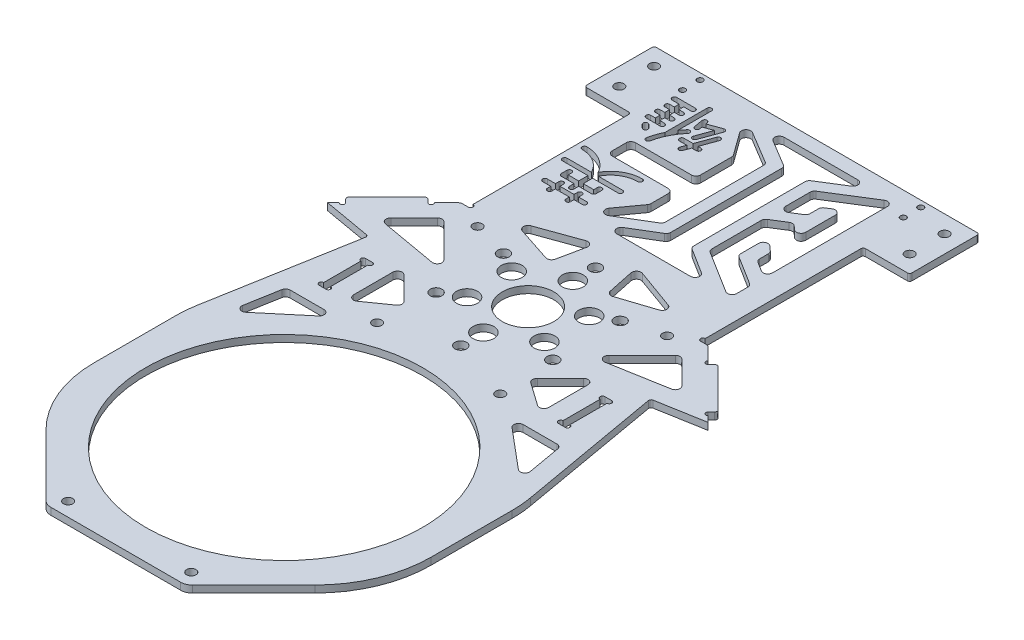
SolidWorks part; units mm, degrees
material "Thornel Mat VMA"
ref_plane "前视基准面" through (0, 0, 0) normal (0, 0, 1) x (1, 0, 0)
ref_plane "上视基准面" through (0, 0, 0) normal (0, 1, 0) x (1, 0, 0)
ref_plane "右视基准面" through (0, 0, 0) normal (1, 0, 0) x (0, 0, -1)
sketch "草图1" plane through (0, 0, 0) normal (0, 1, 0) x (1, 0, 0)
  line L0 (-72.5, 30.0305) -> (-60.7129, 96.8783)
  line L2 (0, 105) -> (0, 0) construction
  line L3 (-29.8887, -60) -> (20.992, -60) construction
  line L4 (30.0305, 72.5) -> (-30.0305, 72.5) construction
  line L5 (-30.0305, 72.5) -> (-72.5, 30.0305) construction
  line L6 (-72.5, 30.0305) -> (-72.5, -30.0305)
  line L7 (-72.5, -30.0305) -> (-30.0305, -72.5)
  line L8 (-30.0305, -72.5) -> (30.0305, -72.5)
  line L9 (30.0305, -72.5) -> (72.5, -30.0305)
  line L10 (72.5, -30.0305) -> (72.5, 30.0305)
  line L11 (72.5, 30.0305) -> (30.0305, 72.5) construction
  line L12 (0, 0) -> (-36.7354, 0) construction
  line L13 (-40.7839, 124.0178) -> (0, 105) construction
  line L14 (-89.43, 93.0743) -> (-127.5, 55.0043) construction
  line L15 (-127.5, 55.0043) -> (-127.5, 46.0679) construction
  line L16 (-78.0025, 104.5017) -> (-81.8916, 100.6126)
  line L17 (-60.3249, 122.1794) -> (-62.4462, 124.3007)
  line L18 (-53.2538, 129.2505) -> (-60.3249, 122.1794)
  line L19 (-81.8916, 100.6126) -> (-60.7129, 96.8783)
  line L20 (-53.2538, 129.2505) -> (-50, 129.2505)
  line L21 (0, -55) -> (0, 55) construction
  line L22 (72.5, 30.0305) -> (60.7129, 96.8783)
  line L23 (62.4462, 124.3007) -> (80.1238, 106.6231)
  line L24 (80.1238, 106.6231) -> (78.0025, 104.5017)
  line L26 (81.8916, 100.6126) -> (60.7129, 96.8783)
  line L27 (53.2538, 129.2505) -> (60.3249, 122.1794)
  line L28 (-80.1238, 106.6231) -> (-78.0025, 104.5017)
  line L29 (-62.4462, 124.3007) -> (-80.1238, 106.6231)
  line L30 (60.3249, 122.1794) -> (62.4462, 124.3007)
  line L31 (78.0025, 104.5017) -> (81.8916, 100.6126)
  line L33 (-50, 129.2505) -> (-50, 199.25)
  line L34 (-50, 199.25) -> (-70, 199.25)
  line L35 (-70, 199.25) -> (-70, 229.25)
  line L36 (-70, 229.25) -> (70, 229.25)
  line L37 (53.2538, 129.2505) -> (50, 129.2505)
  line L38 (50, 129.2505) -> (50, 199.25)
  line L39 (50, 199.25) -> (70, 199.25)
  line L40 (70, 199.25) -> (70, 229.25)
  line L41 (-62.5, 221.75) -> (-62.5, 206.75) construction
  line L42 (-47.5, 226.5) -> (-47.5, 219) construction
  circle A1 centre (0, 0) radius 59.6
  circle A3 centre (0, 105) radius 11.1
  circle A6 centre (-26.5, -66.5) radius 2
  circle A9 centre (26.5, -66.5) radius 2
  circle A11 centre (0, 0) radius 72.5 construction
  circle A12 centre (26.5, 66.5) radius 2
  circle A13 centre (-26.5, 66.5) radius 2
  circle A15 centre (-40.7839, 124.0178) radius 2
  circle A16 centre (40.7839, 124.0178) radius 2
  circle A19 centre (-62.5, 221.75) radius 2
  circle A20 centre (-62.5, 206.75) radius 2
  circle A21 centre (62.5, 206.75) radius 2
  circle A22 centre (62.5, 221.75) radius 2
  circle A24 centre (-47.5, 226.5) radius 1.25
  circle A26 centre (-47.5, 219) radius 1.25
  circle A27 centre (47.5, 219) radius 1.25
  circle A28 centre (47.5, 226.5) radius 1.25
  dimension "D2" = 119.2
  dimension "D3" = 53
  dimension "D4" = 22.2
  dimension "D6" = 60
  dimension "D7" = 4
  dimension "D10" = 145
  dimension "D8" = 6.5
  dimension "D9" = 4
  dimension "D22" = 50
  dimension "D26" = 4
  dimension "D27" = 15
  dimension "D30" = 2.75
  dimension "D32" = 2.5
  dimension "D23" = 229.25
  dimension "D5" = 105
  dimension "D11" = 45
  dimension "D12" = 115
  dimension "D13" = 129.05
  dimension "D14" = 5.5
  dimension "D15" = 127.5
  dimension "D16" = 70
  dimension "D17" = 135
  dimension "D18" = 3
  dimension "D19" = 25
  dimension "D20" = 10
  dimension "D21" = 35
  dimension "D24" = 30
  dimension "D25" = 20
  dimension "D28" = 7.5
  dimension "D29" = 7.5
  dimension "D31" = 15
  dimension "D33" = 7.5
extrude "凸台-拉伸1" add sketch "草图1" along normal blind 3
sketch "草图2" plane through (0, 3, 0) normal (0, 1, 0) x (1, 0, 0)
  line L0 (0, 155) -> (0, 85.2716) construction
  line L3 (0, 0) -> (0, -72.5) construction
  line L15 (-30.0305, -72.5) -> (30.0305, -72.5) construction
  line L17 (0, -55) -> (0, 55) construction
  line L18 (-53, 88) -> (-50, 88)
  line L19 (-53, 88) -> (-53, 68)
  line L20 (-53, 68) -> (-50, 68)
  line L21 (-50, 88) -> (-50, 68)
  line L22 (50, 88) -> (50, 68)
  line L23 (53, 68) -> (50, 68)
  line L24 (53, 88) -> (53, 68)
  line L36 (53, 88) -> (50, 88)
  circle A9 centre (0, 134) radius 2.5
  circle A10 centre (0, 124.25) radius 4.5
  circle A11 centre (0, 105) radius 29 construction
  circle A12 centre (0, 105) radius 19.25 construction
  circle A14 centre (25.1147, 119.5) radius 2.5
  circle A15 centre (16.671, 114.625) radius 4.5
  circle A16 centre (25.1147, 90.5) radius 2.5
  circle A17 centre (16.671, 95.375) radius 4.5
  circle A18 centre (0, 76) radius 2.5
  circle A19 centre (0, 85.75) radius 4.5
  circle A20 centre (-25.1147, 90.5) radius 2.5
  circle A21 centre (-16.671, 95.375) radius 4.5
  circle A22 centre (-25.1147, 119.5) radius 2.5
  circle A23 centre (-16.671, 114.625) radius 4.5
  dimension "D1" = 9
  dimension "D2" = 5
  dimension "D4" = 38.5
  dimension "D5" = 58
  dimension "D6" = 100
  dimension "D10" = 3
  dimension "D3" = 6
  dimension "D11" = 68
  dimension "D16" = 20
extrude "切除-拉伸4" cut sketch "草图2" against normal through all
sketch "草图3" plane through (0, 3, 0) normal (0, 1, 0) x (1, 0, 0)
  line L0 (-53, 88) -> (-53, 68) construction
  line L1 (-50, 68) -> (-50, 88) construction
  line L2 (-78.0025, 104.5017) -> (-81.8916, 100.6126) construction
  line L3 (-53.2538, 129.2505) -> (-60.3249, 122.1794) construction
  line L4 (-50, 199.25) -> (-50, 129.2505) construction
  line L8 (0, -1.65) -> (0, 1.65) construction
  circle A0 centre (-53, 87) radius 1
  circle A1 centre (-50, 87) radius 1
  circle A2 centre (-53, 69) radius 1
  circle A3 centre (-50, 69) radius 1
  circle A20 centre (50, 69) radius 1
  circle A21 centre (53, 69) radius 1
  circle A22 centre (50, 87) radius 1
  circle A23 centre (53, 87) radius 1
  circle A24 centre (-78.7096, 103.7946) radius 1
  circle A25 centre (-59.6177, 122.8865) radius 1
  circle A26 centre (59.6177, 122.8865) radius 1
  circle A27 centre (78.7096, 103.7946) radius 1
  circle A28 centre (-50, 130.2505) radius 1
  circle A29 centre (50, 130.2505) radius 1
  dimension "D1" = 2
extrude "切除-拉伸5" cut sketch "草图3" against normal through all
sketch "草图4" plane through (0, 3, 0) normal (0, 1, 0) x (1, 0, 0)
  line L0 (-59.0922, 60) -> (-37.3955, 60)
  line L1 (-37.3955, 60) -> (-62.8597, 38.6329)
  line L2 (-62.8597, 38.6329) -> (-59.0922, 60)
  line L3 (-51.2259, 119.9646) -> (-31.0288, 99.7676)
  line L4 (-31.0288, 99.7676) -> (-65.368, 105.8225)
  line L5 (-65.368, 105.8225) -> (-51.2259, 119.9646)
  line L6 (-42, 93.5787) -> (-42, 68)
  line L7 (-42, 68) -> (-27, 78.5787)
  line L8 (-27, 78.5787) -> (-42, 93.5787)
  line L9 (-60.7129, 96.8783) -> (-72.5, 30.0305) construction
  line L10 (40, 151.25) -> (40, 160.6877)
  line L11 (-81.8916, 100.6126) -> (-60.7129, 96.8783) construction
  line L12 (-53.2538, 129.2505) -> (-58.9106, 123.5936) construction
  line L13 (-53, 68) -> (-50, 68) construction
  line L14 (-50, 70) -> (-50, 86) construction
  line L15 (40, 223.25) -> (18, 209.4808)
  line L16 (18, 209.4808) -> (18, 194.3138)
  line L17 (18, 194.3138) -> (26, 199.3208)
  line L18 (26, 199.3208) -> (26, 205.0501)
  line L19 (26, 205.0501) -> (32, 208.8053)
  line L20 (32, 208.8053) -> (32, 188.0557)
  line L21 (32, 188.0557) -> (26, 193.4222)
  line L22 (26, 193.4222) -> (18, 188.4152)
  line L23 (18, 188.4152) -> (18, 165.0192)
  line L24 (18, 165.0192) -> (40, 151.25)
  line L25 (32, 171.5932) -> (32, 177.3225)
  line L26 (32, 177.3225) -> (26, 182.6891)
  line L27 (26, 182.6891) -> (26, 169.4499)
  line L28 (26, 169.4499) -> (40, 160.6877)
  line L29 (30.5755, 151.25) -> (-15.2962, 151.25)
  line L30 (-15.2962, 151.25) -> (3, 162.25)
  line L31 (3, 162.25) -> (3, 212.25)
  line L32 (3, 212.25) -> (-15.2962, 223.25)
  line L33 (-15.2962, 223.25) -> (30.5755, 223.25)
  line L34 (30.5755, 223.25) -> (13, 212.25)
  line L35 (13, 212.25) -> (13, 162.25)
  line L36 (13, 162.25) -> (30.5755, 151.25)
  line L45 (-25, 151.25) -> (-2, 165.078)
  line L50 (-2, 165.078) -> (-2, 209.422)
  line L51 (-2, 209.422) -> (-25, 223.25)
  line L52 (-25, 223.25) -> (-12, 205.25)
  line L53 (-12, 205.25) -> (-12, 189.25)
  line L54 (-12, 189.25) -> (-40, 189.25)
  line L55 (-40, 189.25) -> (-40, 179.25)
  line L56 (-40, 179.25) -> (-12, 179.25)
  line L57 (-12, 179.25) -> (-12, 169.25)
  line L58 (-12, 169.25) -> (-25, 151.25)
  line L59 (32, 171.5932) -> (40, 166.5862)
  line L62 (40, 166.5862) -> (40, 223.25)
  line L63 (0, -1.65) -> (0, 1.65) construction
  line L64 (27, 78.5787) -> (42, 93.5787)
  line L65 (42, 68) -> (27, 78.5787)
  line L66 (42, 93.5787) -> (42, 68)
  line L67 (65.368, 105.8225) -> (51.2259, 119.9646)
  line L68 (31.0288, 99.7676) -> (65.368, 105.8225)
  line L69 (51.2259, 119.9646) -> (31.0288, 99.7676)
  line L70 (62.8597, 38.6329) -> (59.0922, 60)
  line L71 (37.3955, 60) -> (62.8597, 38.6329)
  line L72 (59.0922, 60) -> (37.3955, 60)
  line L73 (70, 229.25) -> (-70, 229.25) construction
  line L74 (13, 187.25) -> (3, 187.25) construction
  line L75 (8, 151.25) -> (8, 223.25) construction
  line L76 (32, 188.0557) -> (26, 182.6891) construction
  line L77 (-50, 199.25) -> (-50, 131.2505) construction
  line L78 (50, 131.2505) -> (50, 199.25) construction
  line L79 (-35, 133.7936) -> (-8.7895, 143.25)
  line L80 (-8.7895, 143.25) -> (-12.3301, 126.3564)
  line L81 (-12.3301, 126.3564) -> (-35, 133.7936)
  line L82 (-24.3354, 121.8754) -> (-15.2682, 118.9008) construction
  line L83 (-4.4043, 125.1731) -> (-2.4468, 134.5128) construction
  line L85 (12.3301, 126.3564) -> (35, 133.7936)
  line L86 (8.7895, 143.25) -> (12.3301, 126.3564)
  line L87 (35, 133.7936) -> (8.7895, 143.25)
  circle A0 centre (-25.1147, 119.5) radius 2.5 construction
  circle A1 centre (-16.671, 114.625) radius 4.5 construction
  circle A2 centre (0, 134) radius 2.5 construction
  circle A3 centre (0, 124.25) radius 4.5 construction
  point P18 (8, 187.25)
  point P92 (-3.4256, 129.8429)
  point P94 (0, 229.25)
  point P101 (8, 187.25)
  dimension "D1" = 8
  dimension "D2" = 8
  dimension "D3" = 8
  dimension "D4" = 8
  dimension "D5" = 70
  dimension "D6" = 8
  dimension "D7" = 15
  dimension "D8" = 15
  dimension "D9" = 20
  dimension "D10" = 78
  dimension "D11" = 6
  dimension "D12" = 10
  dimension "D13" = 5
  dimension "D14" = 5
  dimension "D15" = 5
  dimension "D16" = 10
  dimension "D17" = 10
  dimension "D18" = 10
  dimension "D19" = 5
  dimension "D20" = 5
  dimension "D21" = 5
  dimension "D22" = 10
  dimension "D23" = 5
  dimension "D24" = 5
  dimension "D25" = 50
  dimension "D26" = 10
  dimension "D27" = 8
  dimension "D28" = 8
  dimension "D29" = 8
  dimension "D30" = 8
  dimension "D31" = 8
  dimension "D32" = 8
  dimension "D33" = 15
  dimension "D34" = 8
  dimension "D35" = 8
  dimension "D36" = 8
  dimension "D37" = 15
  dimension "D38" = 8
extrude "切除-拉伸7" cut sketch "草图4" against normal through all
sketch "草图5" plane through (0, 3, 0) normal (0, 1, 0) x (1, 0, 0)
  line L1 (-26.5, 155.75) -> (-43.5, 155.75) construction
  line L2 (-26.5, 154.75) -> (-43.5, 154.75)
  line L3 (-26.5, 156.75) -> (-43.5, 156.75)
  line L4 (-31, 153.25) -> (-31, 158.25) construction
  line L5 (-32, 153.25) -> (-32, 158.25)
  line L6 (-30, 153.25) -> (-30, 158.25)
  line L7 (-35, 167.75) -> (-35, 158.75) construction
  line L10 (-28.5, 161.75) -> (-28.5, 164.25) construction
  line L11 (-29.5, 161.75) -> (-29.5, 164.25)
  line L12 (-27.5, 161.75) -> (-27.5, 164.25)
  line L13 (-28.5, 161.75) -> (-41.5, 161.75) construction
  line L14 (-28.5, 160.75) -> (-41.5, 160.75)
  line L15 (-28.5, 162.75) -> (-41.5, 162.75)
  line L16 (-23, 167.75) -> (-47, 167.75) construction
  line L19 (-23, 166.75) -> (-47, 166.75)
  line L20 (-23, 168.75) -> (-47, 168.75)
  line L21 (-50, 199.25) -> (-50, 131.2505) construction
  line L22 (-18.1026, 152.25) -> (-34, 152.25) construction
  line L23 (-34, 167.75) -> (-34, 158.75)
  line L24 (-36, 167.75) -> (-36, 158.75)
  line L25 (-23, 177.25) -> (-47, 177.25) construction
  line L26 (-35, 158.75) -> (-35, 155.75) construction
  line L27 (-41.5, 161.75) -> (-41.5, 164.25) construction
  line L28 (-40.5, 161.75) -> (-40.5, 164.25)
  line L29 (-42.5, 161.75) -> (-42.5, 164.25)
  line L30 (-39, 153.25) -> (-39, 158.25) construction
  line L31 (-38, 153.25) -> (-38, 158.25)
  line L32 (-40, 153.25) -> (-40, 158.25)
  line L33 (-40, 179.25) -> (-12, 179.25) construction
  line L34 (-21.9414, 200.3358) -> (-29.2258, 200.3358) construction
  line L35 (-21.9414, 199.3358) -> (-29.2258, 199.3358)
  line L36 (-21.9414, 201.3358) -> (-29.2258, 201.3358)
  line L37 (-27.0526, 203.8358) -> (-23.9039, 212.4867) construction
  line L38 (-27.9923, 204.1778) -> (-24.8436, 212.8288)
  line L39 (-26.1129, 203.4938) -> (-22.9642, 212.1447)
  line L40 (-23.9039, 212.4867) -> (-30.6527, 210.0304) construction
  line L41 (-23.5619, 211.547) -> (-30.3107, 209.0907)
  line L42 (-24.2459, 213.4264) -> (-30.9947, 210.9701)
  line L43 (-25.8758, 196.8358) -> (-21.6411, 208.4706) construction
  line L44 (-26.8155, 197.1778) -> (-22.5808, 208.8126)
  line L45 (-24.9361, 196.4938) -> (-20.7014, 208.1286)
  line L46 (-30.3054, 208.0608) -> (-31, 212) construction
  line L47 (-31.2902, 207.8871) -> (-31.9848, 211.8264)
  line L48 (-29.3206, 208.2344) -> (-30.0152, 212.1736)
  line L49 (-34.5, 199.2589) -> (-34.5, 217.5) construction
  line L50 (-35.5, 199.2589) -> (-35.5, 217.5)
  line L51 (-33.5, 199.2589) -> (-33.5, 217.5)
  line L52 (-41.2929, 196.8358) -> (-42.7071, 198.25) construction
  line L53 (-42, 196.1287) -> (-43.4142, 197.5429)
  line L54 (-40.5858, 197.5429) -> (-42, 198.9571)
  line L55 (-39, 201.75) -> (-45, 201.75) construction
  line L56 (-39, 200.75) -> (-45, 200.75)
  line L57 (-39, 202.75) -> (-45, 202.75)
  line L58 (-42, 201.75) -> (-42, 214) construction
  line L59 (-43, 201.75) -> (-43, 214)
  line L60 (-41, 201.75) -> (-41, 214)
  line L61 (-38, 214) -> (-46, 214) construction
  line L62 (-38, 213) -> (-46, 213)
  line L63 (-38, 215) -> (-46, 215)
  line L64 (-39, 205.8333) -> (-45, 205.8333) construction
  line L65 (-39, 204.8333) -> (-45, 204.8333)
  line L66 (-39, 206.8333) -> (-45, 206.8333)
  line L67 (-39, 209.9167) -> (-45, 209.9167) construction
  line L68 (-39, 208.9167) -> (-45, 208.9167)
  line L69 (-39, 210.9167) -> (-45, 210.9167)
  line L70 (-45, 205.8333) -> (-45, 209.9167) construction
  line L71 (-70, 199.25) -> (-50, 199.25) construction
  line L72 (-12.0596, 188.2395) -> (-30.8607, 201.4878) construction
  line L73 (-12, 189.25) -> (-40, 189.25) construction
  line L74 (-21.6411, 208.4706) -> (-24.93, 209.6677) construction
  arc A0 (-26.5, 154.75) -> (-26.5, 156.75) centre (-26.5, 155.75) ccw
  arc A1 (-43.5, 156.75) -> (-43.5, 154.75) centre (-43.5, 155.75) ccw
  arc A2 (-32, 153.25) -> (-30, 153.25) centre (-31, 153.25) ccw
  arc A3 (-30, 158.25) -> (-32, 158.25) centre (-31, 158.25) ccw
  arc A6 (-29.5, 161.75) -> (-27.5, 161.75) centre (-28.5, 161.75) ccw
  arc A7 (-27.5, 164.25) -> (-29.5, 164.25) centre (-28.5, 164.25) ccw
  arc A8 (-28.5, 160.75) -> (-28.5, 162.75) centre (-28.5, 161.75) ccw
  arc A9 (-41.5, 162.75) -> (-41.5, 160.75) centre (-41.5, 161.75) ccw
  arc A12 (-23, 166.75) -> (-23, 168.75) centre (-23, 167.75) ccw
  arc A13 (-47, 168.75) -> (-47, 166.75) centre (-47, 167.75) ccw
  arc A14 (-35, 167.75) -> (-23, 176.25) centre (-23, 163.5294) cw construction
  arc A19 (-34, 167.75) -> (-36, 167.75) centre (-35, 167.75) ccw
  arc A20 (-36, 158.75) -> (-34, 158.75) centre (-35, 158.75) ccw
  arc A21 (-23, 177.25) -> (-35.9434, 168.0818) centre (-23, 163.5294) ccw
  arc A26 (-40.5, 161.75) -> (-42.5, 161.75) centre (-41.5, 161.75) cw
  arc A27 (-42.5, 164.25) -> (-40.5, 164.25) centre (-41.5, 164.25) cw
  arc A28 (-38, 153.25) -> (-40, 153.25) centre (-39, 153.25) cw
  arc A29 (-40, 158.25) -> (-38, 158.25) centre (-39, 158.25) cw
  arc A30 (-23, 175.25) -> (-34.0566, 167.4182) centre (-23, 163.5294) ccw
  arc A31 (-23, 175.25) -> (-23, 177.25) centre (-23, 176.25) ccw
  arc A32 (-35.9434, 168.0818) -> (-34.0566, 167.4182) centre (-35, 167.75) ccw
  arc A33 (-35, 167.75) -> (-47, 176.25) centre (-47, 163.5294) ccw construction
  arc A34 (-47, 177.25) -> (-34.0566, 168.0818) centre (-47, 163.5294) cw
  arc A35 (-47, 175.25) -> (-35.9434, 167.4182) centre (-47, 163.5294) cw
  arc A36 (-47, 175.25) -> (-47, 177.25) centre (-47, 176.25) cw
  arc A37 (-34.0566, 168.0818) -> (-35.9434, 167.4182) centre (-35, 167.75) cw
  arc A38 (-21.9414, 199.3358) -> (-21.9414, 201.3358) centre (-21.9414, 200.3358) ccw
  arc A39 (-29.2258, 201.3358) -> (-29.2258, 199.3358) centre (-29.2258, 200.3358) ccw
  arc A40 (-27.9923, 204.1778) -> (-26.1129, 203.4938) centre (-27.0526, 203.8358) ccw
  arc A41 (-22.9642, 212.1447) -> (-24.8436, 212.8288) centre (-23.9039, 212.4867) ccw
  arc A42 (-23.5619, 211.547) -> (-24.2459, 213.4264) centre (-23.9039, 212.4867) ccw
  arc A43 (-30.9947, 210.9701) -> (-30.3107, 209.0907) centre (-30.6527, 210.0304) ccw
  arc A44 (-26.8155, 197.1778) -> (-24.9361, 196.4938) centre (-25.8758, 196.8358) ccw
  arc A45 (-20.7014, 208.1286) -> (-22.5808, 208.8126) centre (-21.6411, 208.4706) ccw
  arc A46 (-31.2902, 207.8871) -> (-29.3206, 208.2344) centre (-30.3054, 208.0608) ccw
  arc A47 (-30.0152, 212.1736) -> (-31.9848, 211.8264) centre (-31, 212) ccw
  arc A48 (-36.5523, 193.25) -> (-31, 204.557) centre (-12.0596, 188.2395) cw construction
  arc A49 (-31.7576, 205.2097) -> (-37.5321, 193.4504) centre (-12.0596, 188.2395) ccw
  arc A50 (-30.2424, 203.9043) -> (-35.5726, 193.0496) centre (-12.0596, 188.2395) ccw
  arc A51 (-30.2424, 203.9043) -> (-31.7576, 205.2097) centre (-31, 204.557) ccw
  arc A52 (-37.5321, 193.4504) -> (-35.5726, 193.0496) centre (-36.5523, 193.25) ccw
  arc A53 (-35.5, 199.2589) -> (-33.5, 199.2589) centre (-34.5, 199.2589) ccw
  arc A54 (-33.5, 217.5) -> (-35.5, 217.5) centre (-34.5, 217.5) ccw
  arc A55 (-42, 196.1287) -> (-40.5858, 197.5429) centre (-41.2929, 196.8358) ccw
  arc A56 (-42, 198.9571) -> (-43.4142, 197.5429) centre (-42.7071, 198.25) ccw
  arc A57 (-39, 200.75) -> (-39, 202.75) centre (-39, 201.75) ccw
  arc A58 (-45, 202.75) -> (-45, 200.75) centre (-45, 201.75) ccw
  arc A59 (-43, 201.75) -> (-41, 201.75) centre (-42, 201.75) ccw
  arc A60 (-41, 214) -> (-43, 214) centre (-42, 214) ccw
  arc A61 (-38, 213) -> (-38, 215) centre (-38, 214) ccw
  arc A62 (-46, 215) -> (-46, 213) centre (-46, 214) ccw
  arc A63 (-39, 204.8333) -> (-39, 206.8333) centre (-39, 205.8333) ccw
  arc A64 (-45, 206.8333) -> (-45, 204.8333) centre (-45, 205.8333) ccw
  arc A65 (-39, 208.9167) -> (-39, 210.9167) centre (-39, 209.9167) ccw
  arc A66 (-45, 210.9167) -> (-45, 208.9167) centre (-45, 209.9167) ccw
  circle A67 centre (-47.5, 219) radius 1.25 construction
  circle A68 centre (-28.9367, 205.9687) radius 1.5 construction
  circle A69 centre (-29.3047, 203.4959) radius 1 construction
  circle A70 centre (-30.8607, 201.4878) radius 1 construction
  point P2 (-35, 155.75)
  point P7 (-31, 155.75)
  point P14 (-35, 167.75)
  point P21 (-28.5, 163)
  point P28 (-35, 161.75)
  point P39 (-30.3527, 173.9097)
  point P45 (-35, 163.25)
  point P51 (-28.5, 165.25)
  point P56 (-35, 157.75)
  point P60 (-25.5836, 200.3358)
  point P63 (-31, 159.25)
  point P66 (-25.4783, 208.1613)
  point P74 (-41.5, 163)
  point P81 (-39, 155.75)
  point P89 (-39.6473, 173.9097)
  point P99 (-27.2783, 211.2586)
  point P106 (-23.7584, 202.6532)
  point P115 (-30.6527, 210.0304)
  point P123 (-34.5, 199.2589)
  point P130 (-34.5, 208.3795)
  point P135 (-42, 197.5429)
  point P142 (-42, 201.75)
  point P151 (-42, 207.875)
  point P156 (-42, 214)
  point P164 (-42, 205.8333)
  point P171 (-42, 209.9167)
  point P179 (-45, 207.875)
  point P183 (-37, 214)
  dimension "D2" = 1
  dimension "D6" = 2
  dimension "D14" = 3.5
  dimension "D16" = 3
  dimension "D18" = 4
  dimension "D21" = 2.5
  dimension "D30" = 2.5
  dimension "D31" = 3
  dimension "D32" = 2.5
  dimension "D34" = 2
  dimension "D35" = 1.5
  dimension "D36" = 2.5
  dimension "D33" = 4
  dimension "D37" = 2.5
  dimension "D38" = 25
  dimension "D39" = 3
  dimension "D40" = 2.5
  dimension "D1" = 2
  dimension "D3" = 1.5
  dimension "D4" = 15
  dimension "D5" = 1.5
  dimension "D7" = 5
  dimension "D8" = 4.5
  dimension "D9" = 2
  dimension "D10" = 2.5
  dimension "D11" = 24
  dimension "D12" = 24
  dimension "D13" = 25
  dimension "D15" = 2
  dimension "D17" = 1.5
  dimension "D19" = 6
  dimension "D20" = 8
  dimension "D22" = 10
  dimension "D23" = 20
  dimension "D24" = 1.5
  dimension "D25" = 70
  dimension "D26" = 4
  dimension "D27" = 1.5
  dimension "D28" = 2
  dimension "D29" = 45
  dimension "D41" = 5
extrude "切除-拉伸8" cut sketch "草图5" against normal through all contours L3 A1 L2 A0 | L6 A3 L5 A2 | A29 L31 A28 L32 | L14 A9 L15 A8 | L23 A20 L24 A19 | L11 A7 L12 A6 | L19 A13 L20 A12 | A21 A32 A30 A31 | A34 A37 A35 A36 | L29 A27 L28 A26 | L45 A45 L44 A44 | L35 A39 L36 A38 | L39 A41 L38 A40 | L41 A43 L42 A42 | L48 A47 L47 A46 | A49 A52 A50 A51 | L51 A54 L50 A53 | L62 A62 L63 A61 | L69 A66 L68 A65 | L66 A64 L65 A63 | L57 A58 L56 A57 | L60 A60 L59 A59 | L54 A56 L53 A55
fillet "圆角1" radius 5 2 edges at (30.0305, 1.5, 72.5) (-30.0305, 1.5, 72.5)
fillet "圆角2" radius 1 12 edges at (60.7129, 1.5, -96.8783) (80.1238, 1.5, -106.6231) (62.4462, 1.5, -124.3007) (-60.7129, 1.5, -96.8783) (-80.1238, 1.5, -106.6231) (-62.4462, 1.5, -124.3007) (50, 1.5, -199.25) (70, 1.5, -199.25) (70, 1.5, -229.25) (-70, 1.5, -229.25) (-70, 1.5, -199.25) (-50, 1.5, -199.25)
fillet "圆角3" radius 50 4 edges at (72.5, 1.5, 30.0305) (72.5, 1.5, -30.0305) (-72.5, 1.5, -30.0305) (-72.5, 1.5, 30.0305)
fillet "圆角5" radius 2 61 edges at (-8.7895, 1.5, -143.25) (-12.3301, 1.5, -126.3564) (-35, 1.5, -133.7936) (42, 1.5, -93.5787) (42, 1.5, -68) (27, 1.5, -78.5787) (-12, 1.5, -179.25) (-40, 1.5, -179.25) (-40, 1.5, -189.25) (-12, 1.5, -189.25) (-12, 1.5, -205.25) (-25, 1.5, -223.25) (-2, 1.5, -209.422) (-2, 1.5, -165.078) (-25, 1.5, -151.25) (-12, 1.5, -169.25) (51.2259, 1.5, -119.9646) (31.0288, 1.5, -99.7676) (18, 1.5, -188.4152) (26, 1.5, -193.4222) (32, 1.5, -188.0557) (32, 1.5, -208.8053) (26, 1.5, -205.0501) (26, 1.5, -199.3208) (18, 1.5, -194.3138) (18, 1.5, -209.4808) (40, 1.5, -223.25) (40, 1.5, -166.5862) (32, 1.5, -171.5932) (32, 1.5, -177.3225) (26, 1.5, -182.6891) (26, 1.5, -169.4499) (40, 1.5, -160.6877) (40, 1.5, -151.25) (18, 1.5, -165.0192) (-15.2962, 1.5, -223.25) (30.5755, 1.5, -223.25) (13, 1.5, -212.25) (13, 1.5, -162.25) (30.5755, 1.5, -151.25) (-15.2962, 1.5, -151.25) (3, 1.5, -162.25) (3, 1.5, -212.25) (-42, 1.5, -68) (-42, 1.5, -93.5787) (-27, 1.5, -78.5787) (-31.0288, 1.5, -99.7676) (-65.368, 1.5, -105.8225) (-51.2259, 1.5, -119.9646) (59.0922, 1.5, -60) (62.8597, 1.5, -38.6329) (37.3955, 1.5, -60) (35, 1.5, -133.7936) (12.3301, 1.5, -126.3564) (8.7895, 1.5, -143.25) (-37.3955, 1.5, -60) (-62.8597, 1.5, -38.6329) (-59.0922, 1.5, -60) (65.368, 1.5, -105.8225) (-53.2538, 1.5, -129.2505) (53.2538, 1.5, -129.2505)
